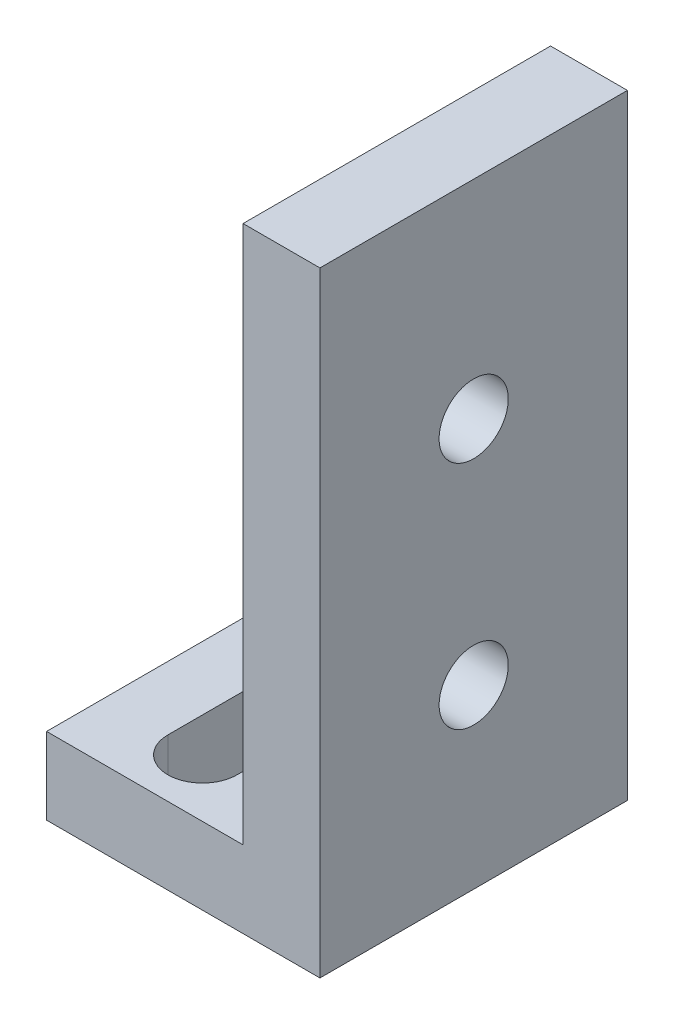
SolidWorks part; units mm, degrees
ref_plane "Plano frontal" through (0, 0, 0) normal (0, 0, 1) x (1, 0, 0)
ref_plane "Plano superior" through (0, 0, 0) normal (0, 1, 0) x (1, 0, 0)
ref_plane "Plano direito" through (0, 0, 0) normal (1, 0, 0) x (0, 0, -1)
sketch "Esboço1" plane through (0, 0, 0) normal (0, 0, 1) x (1, 0, 0)
  line L0 (0, 0) -> (0, 5)
  line L1 (0, 5) -> (12.78, 5)
  line L2 (12.78, 5) -> (12.78, 40)
  line L3 (12.78, 40) -> (17.78, 40)
  line L4 (17.78, 40) -> (17.78, 0)
  line L5 (17.78, 0) -> (0, 0)
  dimension "D1" = 17.78
  dimension "D2" = 40
  dimension "D3" = 5
  dimension "D4" = 5
extrude "Ressalto-extrusão1" add sketch "Esboço1" along normal blind 20
sketch "Esboço2" plane through (0, 5, 0) normal (0, 1, 0) x (1, 0, 0)
  line L0 (6.39, -3.75) -> (6.39, -16.25) construction
  line L1 (8.64, -3.75) -> (8.64, -16.25)
  line L2 (4.14, -3.75) -> (4.14, -16.25)
  line L3 (0, -20) -> (0, 0) construction
  line L4 (12.78, -20) -> (0, -20) construction
  arc A0 (8.64, -3.75) -> (4.14, -3.75) centre (6.39, -3.75) ccw
  arc A1 (4.14, -16.25) -> (8.64, -16.25) centre (6.39, -16.25) ccw
  point P2 (6.39, -10)
  point P11 (13.25, -14.9441)
  dimension "D4" = 12.5
  dimension "D2" = 2.25
  dimension "D1" = 6.39
  dimension "D3" = 10
extrude "Corte-extrusão1" cut sketch "Esboço2" against normal through all
sketch "Esboço3" plane through (12.78, 0, 0) normal (-1, 0, 0) x (0, 0, 1)
  line L0 (20, 40) -> (20, 5) construction
  line L1 (20, 40) -> (0, 40) construction
  circle A0 centre (10, 26.5) radius 2.25
  circle A1 centre (10, 11.5) radius 2.25
  point P8 (0, 0)
  dimension "D3" = 4.5
  dimension "D1" = 15
  dimension "D2" = 10
  dimension "D4" = 13.5
extrude "Corte-extrusão2" cut sketch "Esboço3" against normal through all
